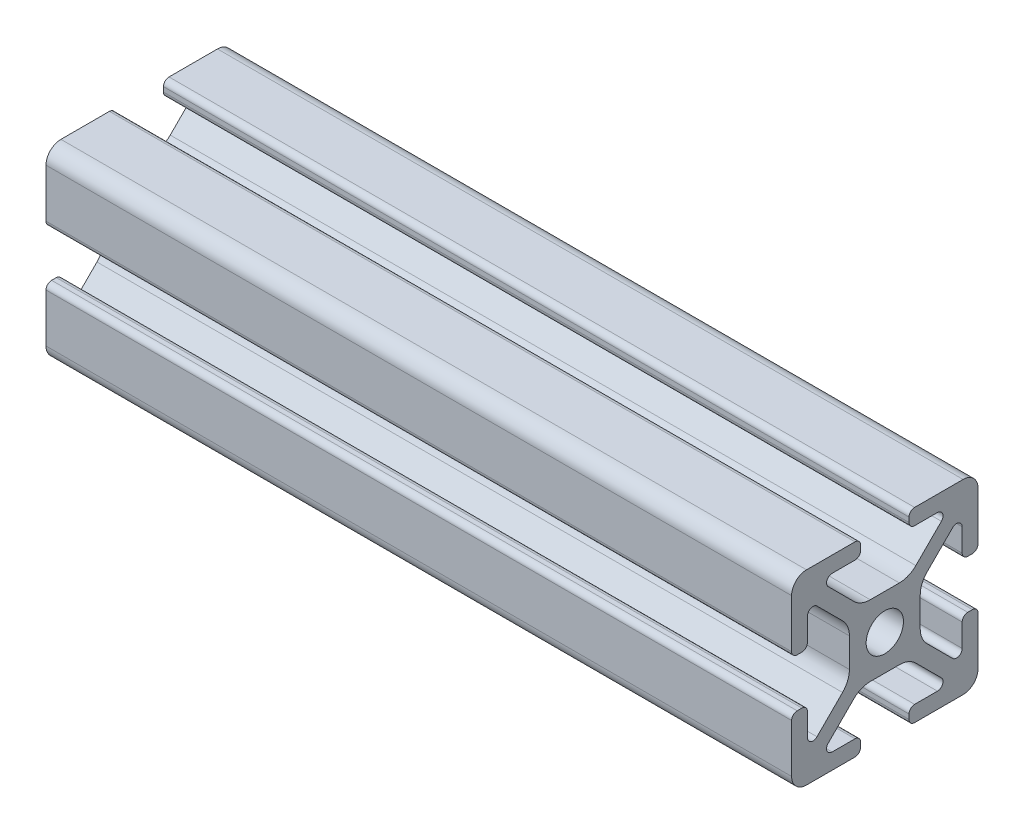
SolidWorks part; units mm, degrees
ref_plane "Front Plane" through (0, 0, 0) normal (0, 0, 1) x (1, 0, 0)
ref_plane "Top Plane" through (0, 0, 0) normal (0, 1, 0) x (1, 0, 0)
ref_plane "Right Plane" through (0, 0, 0) normal (1, 0, 0) x (0, 0, -1)
sketch "Sketch1" plane through (0, 0, 0) normal (1, 0, 0) x (0, 0, -1)
  line L0 (0, -12.7) -> (0, 12.7) construction
  line L1 (-7.874, 12.7) -> (7.874, 12.7) construction
  line L2 (-12.7, 0) -> (12.7, 0) construction
  line L3 (-7.874, 12.7) -> (-7.874, 4.826) construction
  line L4 (-3.302, 12.7) -> (3.302, 12.7) construction
  line L5 (-12.7, -12.7) -> (12.7, -12.7) construction
  line L6 (-12.7, 12.7) -> (12.7, 12.7) construction
  circle A0 centre (0, 0) radius 2.54 construction
  point P7 (0, 12.7)
  point P10 (0, 0)
  point P13 (0, 0)
  point P16 (0, 12.7)
  point P17 (-3.302, 12.7)
  point P18 (3.302, 12.7)
  point P21 (0, -12.7)
  point P24 (0, 12.7)
  dimension "Center Hole Diameter" = 5.08
  dimension "Rail Width" = 25.4
  dimension "Rail Height" = 25.4
  dimension "T-Slot Depth" = 7.874
  dimension "D1" = 15.748
  dimension "T-Slot Width" = 6.604
  dimension "D2" = 12.7
sketch "Sketch2" plane through (0, 0, 0) normal (0, 0, 1) x (1, 0, 0)
  line L0 (-50.8, 0) -> (50.8, 0) construction
  line L1 (0, 0) -> (0, 26.104) construction
  line L2 (50.8, -12.7) -> (50.8, 12.7) construction
  line L3 (-50.8, -12.7) -> (-50.8, 12.7) construction
  point P3 (-12.7, 0)
  point P8 (0, 0)
  point P9 (12.7, 0)
  point P12 (50.8, 0)
  point P15 (-50.8, 0)
  dimension "Length" = 101.6
  dimension "D1" = 38.1
  dimension "D2" = 25.4
sketch "Sketch3" plane through (0, 0, 0) normal (1, 0, 0) x (0, 0, -1)
  line L0 (0, 4.826) -> (1.9842, 4.826)
  line L1 (0, -12.7) -> (0, 12.7) construction
  line L2 (4.2293, 5.7559) -> (7.7135, 9.2402)
  line L6 (7.1747, 10.541) -> (4.064, 10.541)
  line L7 (3.302, 11.303) -> (3.302, 11.938)
  line L8 (-7.874, 12.7) -> (7.874, 12.7) construction
  line L10 (0, 0) -> (12.7, 12.7) construction
  line L13 (0, 4.826) -> (0, 2.54)
  line L14 (4.826, 0) -> (2.54, 0)
  line L31 (4.826, 0) -> (4.826, 1.9842)
  line L32 (4.064, 12.7) -> (10.668, 12.7)
  line L33 (-12.7, 0) -> (12.7, 0) construction
  line L34 (-12.7, 12.7) -> (12.7, 12.7) construction
  line L35 (5.7559, 4.2293) -> (9.2402, 7.7135)
  line L36 (0, 12.7) -> (12.7, 12.7) construction
  line L37 (12.7, 12.7) -> (12.7, 8.0234) construction
  line L38 (11.303, 3.302) -> (11.938, 3.302)
  line L39 (10.541, 7.1747) -> (10.541, 4.064)
  line L40 (12.7, 10.668) -> (12.7, 4.064)
  arc A0 (2.54, 0) -> (0, 2.54) centre (0, 0) ccw
  arc A1 (1.9842, 4.826) -> (4.2293, 5.7559) centre (1.9842, 8.001) ccw
  circle A2 centre (0, 0) radius 2.54 construction
  arc A7 (3.302, 11.938) -> (4.064, 12.7) centre (4.064, 11.938) cw
  arc A8 (4.064, 10.541) -> (3.302, 11.303) centre (4.064, 11.303) cw
  arc A14 (4.826, 1.9842) -> (5.7559, 4.2293) centre (8.001, 1.9842) cw
  arc A16 (10.668, 12.7) -> (12.7, 10.668) centre (10.668, 10.668) cw
  arc A17 (7.1747, 10.541) -> (7.7135, 9.2402) centre (7.1747, 9.779) cw
  arc A18 (10.541, 7.1747) -> (9.2402, 7.7135) centre (9.779, 7.1747) ccw
  arc A19 (10.541, 4.064) -> (11.303, 3.302) centre (11.303, 4.064) ccw
  arc A20 (11.938, 3.302) -> (12.7, 4.064) centre (11.938, 4.064) ccw
  point P37 (3.2994, 4.826)
  point P49 (12.7, 3.302)
  point P52 (3.302, 12.7)
  point P55 (3.302, 10.541)
  dimension "D4" = 3.175
  dimension "D9" = 2.159
  dimension "D12" = 0.762
  dimension "D3" = 2.032
  dimension "D8" = 0.762
  dimension "D2" = 45
  dimension "D5" = 0
  dimension "D6" = 45
  dimension "D7" = 2.159
extrude "Boss-Extrude1" add sketch "Sketch3" against normal up to vertex (50.8 mm away) and the other way up to vertex (50.8 mm away) up to point (-50.8, 0, 0) other way up to point (50.8, 0, 0)
mirror "Mirror1" about plane through (0, 0, 0) normal (0, 1, 0) of bodies 104
mirror "Mirror2" about plane through (0, 0, 0) normal (0, 0, 1) of bodies 105
equation "\"D1@Sketch2\"=\"Rail Height@Sketch1\"*1.5"
equation "\"D2@Sketch2\"=\"Rail Height@Sketch1\""
